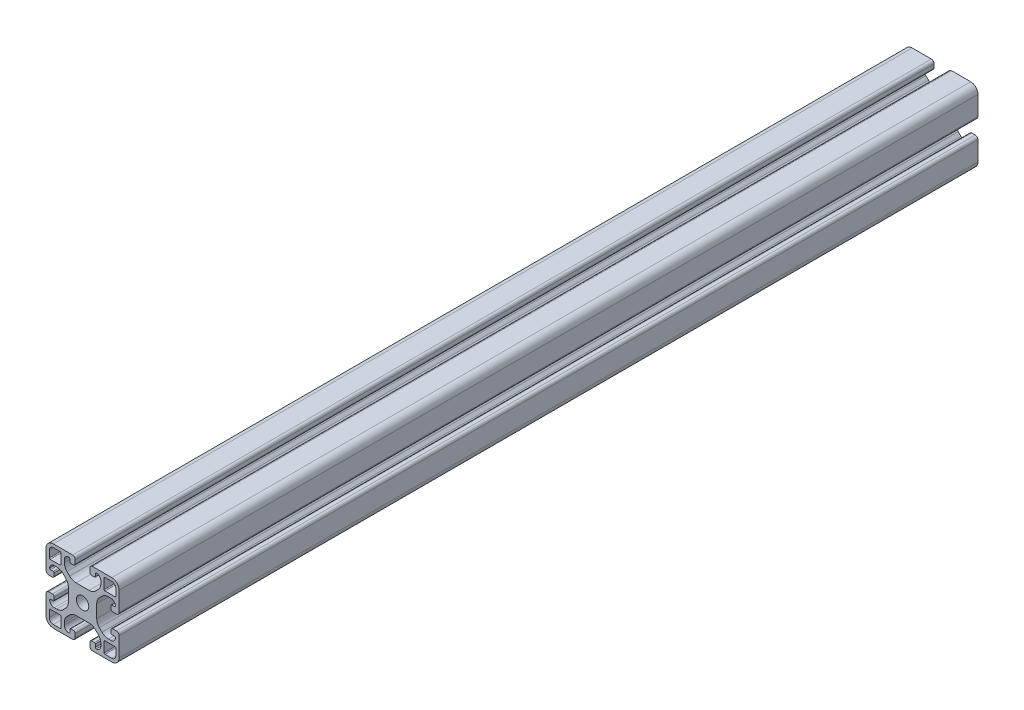
SolidWorks part; units mm, degrees
ref_plane "Plan de face" through (0, 0, 0) normal (0, 0, 1) x (1, 0, 0)
ref_plane "Plan de dessus" through (0, 0, 0) normal (0, 1, 0) x (1, 0, 0)
ref_plane "Plan de droite" through (0, 0, 0) normal (1, 0, 0) x (0, 0, -1)
ref_plane "Plan1" through (0, 0, -30) normal (0, 0, -1) x (-1, 0, 0)
sketch "Esquisse1" plane through (0, 0, -30) normal (0, 0, -1) x (-1, 0, 0)
  line L0 (-4.5, 15) -> (-4.5, 13.5)
  line L1 (-4, 13) -> (-2.5, 13)
  line L2 (-4.5, 10) -> (-5.8076, 10)
  line L3 (-9.3431, 11.4645) -> (-10.7855, 12.9069)
  line L4 (-12.25, 16.4424) -> (-12.25, 23.5576)
  line L5 (-10.7855, 27.0931) -> (-9.3431, 28.5355)
  line L6 (-5.8076, 30) -> (-4.5, 30)
  line L7 (-2.5, 27) -> (-4, 27)
  line L8 (-4.5, 26.5) -> (-4.5, 25)
  line L9 (-3.5, 24) -> (-1.5, 24)
  line L10 (0, 25.5) -> (0, 36)
  line L11 (-4, 40) -> (-14.5, 40)
  line L12 (-16, 38.5) -> (-16, 36.5)
  line L13 (-15, 35.5) -> (-13.5, 35.5)
  line L14 (-13, 36) -> (-13, 37.5)
  line L15 (-10, 35.5) -> (-10, 34.1924)
  line L16 (-11.4645, 30.6569) -> (-12.9069, 29.2145)
  line L17 (-16.4424, 27.75) -> (-23.5576, 27.75)
  line L18 (-27.0931, 29.2145) -> (-28.5355, 30.6569)
  line L19 (-30, 34.1924) -> (-30, 35.5)
  line L20 (-27, 37.5) -> (-27, 36)
  line L21 (-26.5, 35.5) -> (-25, 35.5)
  line L22 (-24, 36.5) -> (-24, 38.5)
  line L23 (-25.5, 40) -> (-36, 40)
  line L24 (-40, 36) -> (-40, 25.5)
  line L25 (-38.5, 24) -> (-36.5, 24)
  line L26 (-35.5, 25) -> (-35.5, 26.5)
  line L27 (-36, 27) -> (-37.5, 27)
  line L28 (-35.5, 30) -> (-34.1924, 30)
  line L29 (-30.6569, 28.5355) -> (-29.2145, 27.0931)
  line L30 (-27.75, 23.5576) -> (-27.75, 16.4424)
  line L31 (-29.2145, 12.9069) -> (-30.6569, 11.4645)
  line L32 (-34.1924, 10) -> (-35.5, 10)
  line L33 (-37.5, 13) -> (-36, 13)
  line L34 (-35.5, 13.5) -> (-35.5, 15)
  line L35 (-36.5, 16) -> (-38.5, 16)
  line L36 (-40, 14.5) -> (-40, 4)
  line L37 (-36, 0) -> (-25.5, 0)
  line L38 (-24, 1.5) -> (-24, 3.5)
  line L39 (-25, 4.5) -> (-26.5, 4.5)
  line L40 (-27, 4) -> (-27, 2.5)
  line L41 (-30, 4.5) -> (-30, 5.8076)
  line L42 (-28.5355, 9.3431) -> (-27.0931, 10.7855)
  line L43 (-23.5576, 12.25) -> (-16.4424, 12.25)
  line L44 (-12.9069, 10.7855) -> (-11.4645, 9.3431)
  line L45 (-10, 5.8076) -> (-10, 4.5)
  line L46 (-13, 2.5) -> (-13, 4)
  line L47 (-13.5, 4.5) -> (-15, 4.5)
  line L48 (-16, 3.5) -> (-16, 1.5)
  line L49 (-14.5, 0) -> (-4, 0)
  line L50 (0, 4) -> (0, 14.5)
  line L51 (-1.5, 16) -> (-3.5, 16)
  line L52 (-4, 1.8) -> (-7.7, 1.8)
  line L53 (-8.2, 2.3) -> (-8.2, 7.7)
  line L54 (-7.7, 8.2) -> (-2.3, 8.2)
  line L55 (-1.8, 7.7) -> (-1.8, 4)
  line L56 (-38.2, 4) -> (-38.2, 7.7)
  line L57 (-37.7, 8.2) -> (-32.3, 8.2)
  line L58 (-31.8, 7.7) -> (-31.8, 2.3)
  line L59 (-32.3, 1.8) -> (-36, 1.8)
  line L60 (-36, 38.2) -> (-32.3, 38.2)
  line L61 (-31.8, 37.7) -> (-31.8, 32.3)
  line L62 (-32.3, 31.8) -> (-37.7, 31.8)
  line L63 (-38.2, 32.3) -> (-38.2, 36)
  line L64 (-1.8, 36) -> (-1.8, 32.3)
  line L65 (-2.3, 31.8) -> (-7.7, 31.8)
  line L66 (-8.2, 32.3) -> (-8.2, 37.7)
  line L67 (-7.7, 38.2) -> (-4, 38.2)
  arc A0 (-4.5, 13.5) -> (-4, 13) centre (-4, 13.5) ccw
  arc A1 (-2.5, 13) -> (-2, 12.5) centre (-2.5, 12.5) cw
  arc A2 (-2, 12.5) -> (-4.5, 10) centre (-4.5, 12.5) cw
  arc A3 (-5.8076, 10) -> (-9.3431, 11.4645) centre (-5.8076, 15) cw
  arc A4 (-10.7855, 12.9069) -> (-12.25, 16.4424) centre (-7.25, 16.4424) cw
  arc A5 (-12.25, 23.5576) -> (-10.7855, 27.0931) centre (-7.25, 23.5576) cw
  arc A6 (-9.3431, 28.5355) -> (-5.8076, 30) centre (-5.8076, 25) cw
  arc A7 (-4.5, 30) -> (-2, 27.5) centre (-4.5, 27.5) cw
  arc A8 (-2, 27.5) -> (-2.5, 27) centre (-2.5, 27.5) cw
  arc A9 (-4, 27) -> (-4.5, 26.5) centre (-4, 26.5) ccw
  arc A10 (-4.5, 25) -> (-3.5, 24) centre (-3.5, 25) ccw
  arc A11 (-1.5, 24) -> (0, 25.5) centre (-1.5, 25.5) ccw
  arc A12 (0, 36) -> (-4, 40) centre (-4, 36) ccw
  arc A13 (-14.5, 40) -> (-16, 38.5) centre (-14.5, 38.5) ccw
  arc A14 (-16, 36.5) -> (-15, 35.5) centre (-15, 36.5) ccw
  arc A15 (-13.5, 35.5) -> (-13, 36) centre (-13.5, 36) ccw
  arc A16 (-13, 37.5) -> (-12.5, 38) centre (-12.5, 37.5) cw
  arc A17 (-12.5, 38) -> (-10, 35.5) centre (-12.5, 35.5) cw
  arc A18 (-10, 34.1924) -> (-11.4645, 30.6569) centre (-15, 34.1924) cw
  arc A19 (-12.9069, 29.2145) -> (-16.4424, 27.75) centre (-16.4424, 32.75) cw
  arc A20 (-23.5576, 27.75) -> (-27.0931, 29.2145) centre (-23.5576, 32.75) cw
  arc A21 (-28.5355, 30.6569) -> (-30, 34.1924) centre (-25, 34.1924) cw
  arc A22 (-30, 35.5) -> (-27.5, 38) centre (-27.5, 35.5) cw
  arc A23 (-27.5, 38) -> (-27, 37.5) centre (-27.5, 37.5) cw
  arc A24 (-27, 36) -> (-26.5, 35.5) centre (-26.5, 36) ccw
  arc A25 (-25, 35.5) -> (-24, 36.5) centre (-25, 36.5) ccw
  arc A26 (-24, 38.5) -> (-25.5, 40) centre (-25.5, 38.5) ccw
  arc A27 (-36, 40) -> (-40, 36) centre (-36, 36) ccw
  arc A28 (-40, 25.5) -> (-38.5, 24) centre (-38.5, 25.5) ccw
  arc A29 (-36.5, 24) -> (-35.5, 25) centre (-36.5, 25) ccw
  arc A30 (-35.5, 26.5) -> (-36, 27) centre (-36, 26.5) ccw
  arc A31 (-37.5, 27) -> (-38, 27.5) centre (-37.5, 27.5) cw
  arc A32 (-38, 27.5) -> (-35.5, 30) centre (-35.5, 27.5) cw
  arc A33 (-34.1924, 30) -> (-30.6569, 28.5355) centre (-34.1924, 25) cw
  arc A34 (-29.2145, 27.0931) -> (-27.75, 23.5576) centre (-32.75, 23.5576) cw
  arc A35 (-27.75, 16.4424) -> (-29.2145, 12.9069) centre (-32.75, 16.4424) cw
  arc A36 (-30.6569, 11.4645) -> (-34.1924, 10) centre (-34.1924, 15) cw
  arc A37 (-35.5, 10) -> (-38, 12.5) centre (-35.5, 12.5) cw
  arc A38 (-38, 12.5) -> (-37.5, 13) centre (-37.5, 12.5) cw
  arc A39 (-36, 13) -> (-35.5, 13.5) centre (-36, 13.5) ccw
  arc A40 (-35.5, 15) -> (-36.5, 16) centre (-36.5, 15) ccw
  arc A41 (-38.5, 16) -> (-40, 14.5) centre (-38.5, 14.5) ccw
  arc A42 (-40, 4) -> (-36, 0) centre (-36, 4) ccw
  arc A43 (-25.5, 0) -> (-24, 1.5) centre (-25.5, 1.5) ccw
  arc A44 (-24, 3.5) -> (-25, 4.5) centre (-25, 3.5) ccw
  arc A45 (-26.5, 4.5) -> (-27, 4) centre (-26.5, 4) ccw
  arc A46 (-27, 2.5) -> (-27.5, 2) centre (-27.5, 2.5) cw
  arc A47 (-27.5, 2) -> (-30, 4.5) centre (-27.5, 4.5) cw
  arc A48 (-30, 5.8076) -> (-28.5355, 9.3431) centre (-25, 5.8076) cw
  arc A49 (-27.0931, 10.7855) -> (-23.5576, 12.25) centre (-23.5576, 7.25) cw
  arc A50 (-16.4424, 12.25) -> (-12.9069, 10.7855) centre (-16.4424, 7.25) cw
  arc A51 (-11.4645, 9.3431) -> (-10, 5.8076) centre (-15, 5.8076) cw
  arc A52 (-10, 4.5) -> (-12.5, 2) centre (-12.5, 4.5) cw
  arc A53 (-12.5, 2) -> (-13, 2.5) centre (-12.5, 2.5) cw
  arc A54 (-13, 4) -> (-13.5, 4.5) centre (-13.5, 4) ccw
  arc A55 (-15, 4.5) -> (-16, 3.5) centre (-15, 3.5) ccw
  arc A56 (-16, 1.5) -> (-14.5, 0) centre (-14.5, 1.5) ccw
  arc A57 (-4, 0) -> (0, 4) centre (-4, 4) ccw
  arc A58 (0, 14.5) -> (-1.5, 16) centre (-1.5, 14.5) ccw
  arc A59 (-3.5, 16) -> (-4.5, 15) centre (-3.5, 15) ccw
  circle A60 centre (-20, 20) radius 3.4
  arc A61 (-1.8, 4) -> (-4, 1.8) centre (-4, 4) cw
  arc A62 (-7.7, 1.8) -> (-8.2, 2.3) centre (-7.7, 2.3) cw
  arc A63 (-8.2, 7.7) -> (-7.7, 8.2) centre (-7.7, 7.7) cw
  arc A64 (-2.3, 8.2) -> (-1.8, 7.7) centre (-2.3, 7.7) cw
  arc A65 (-36, 1.8) -> (-38.2, 4) centre (-36, 4) cw
  arc A66 (-38.2, 7.7) -> (-37.7, 8.2) centre (-37.7, 7.7) cw
  arc A67 (-32.3, 8.2) -> (-31.8, 7.7) centre (-32.3, 7.7) cw
  arc A68 (-31.8, 2.3) -> (-32.3, 1.8) centre (-32.3, 2.3) cw
  arc A69 (-38.2, 36) -> (-36, 38.2) centre (-36, 36) cw
  arc A70 (-32.3, 38.2) -> (-31.8, 37.7) centre (-32.3, 37.7) cw
  arc A71 (-31.8, 32.3) -> (-32.3, 31.8) centre (-32.3, 32.3) cw
  arc A72 (-37.7, 31.8) -> (-38.2, 32.3) centre (-37.7, 32.3) cw
  arc A73 (-4, 38.2) -> (-1.8, 36) centre (-4, 36) cw
  arc A74 (-1.8, 32.3) -> (-2.3, 31.8) centre (-2.3, 32.3) cw
  arc A75 (-7.7, 31.8) -> (-8.2, 32.3) centre (-7.7, 32.3) cw
  arc A76 (-8.2, 37.7) -> (-7.7, 38.2) centre (-7.7, 37.7) cw
extrude "Boss.-Extru.1" add sketch "Esquisse1" against normal blind 470
